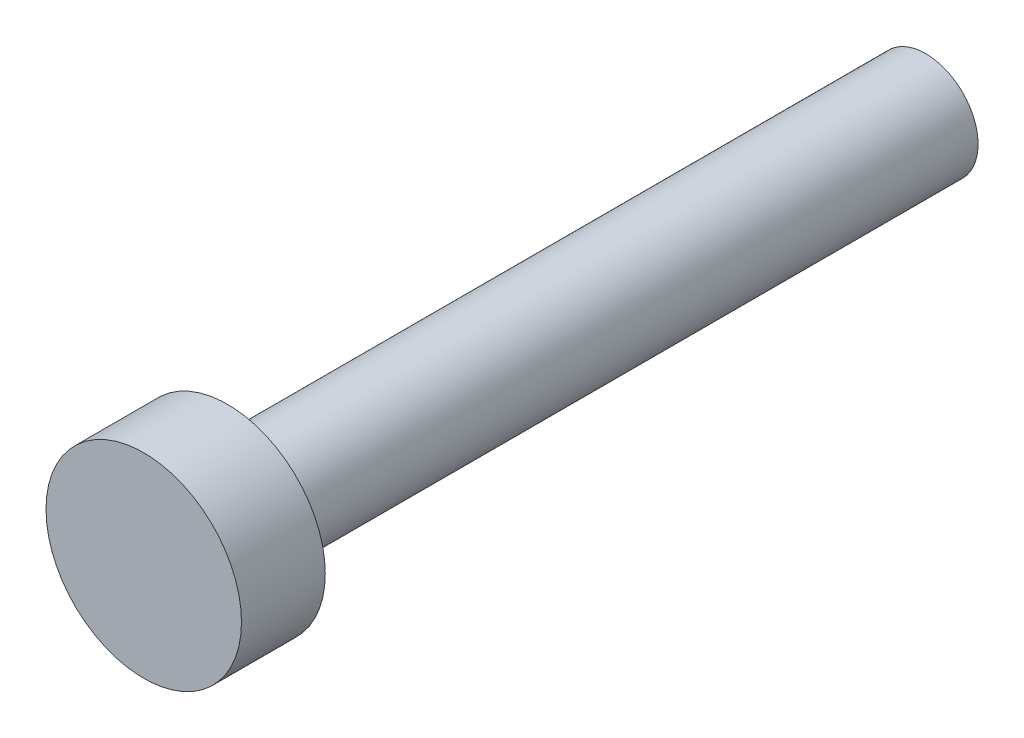
SolidWorks part; units mm, degrees
ref_plane "Plan de face" through (0, 0, 0) normal (0, 0, 1) x (1, 0, 0)
ref_plane "Plan de dessus" through (0, 0, 0) normal (0, 1, 0) x (1, 0, 0)
ref_plane "Plan de droite" through (0, 0, 0) normal (1, 0, 0) x (0, 0, -1)
sketch "Esquisse1" plane through (0, 0, 0) normal (0, 0, 1) x (1, 0, 0)
  circle A0 centre (0, 0) radius 2.8
  dimension "D1" = 5.6
extrude "Boss.-Extru.1" add sketch "Esquisse1" along normal blind 2.4
sketch "Esquisse2" plane through (0, 0, 0) normal (0, 0, -1) x (-1, 0, 0)
  circle A0 centre (0, 0) radius 1.5
  dimension "D1" = 3
extrude "Boss.-Extru.2" add sketch "Esquisse2" along normal blind 20
